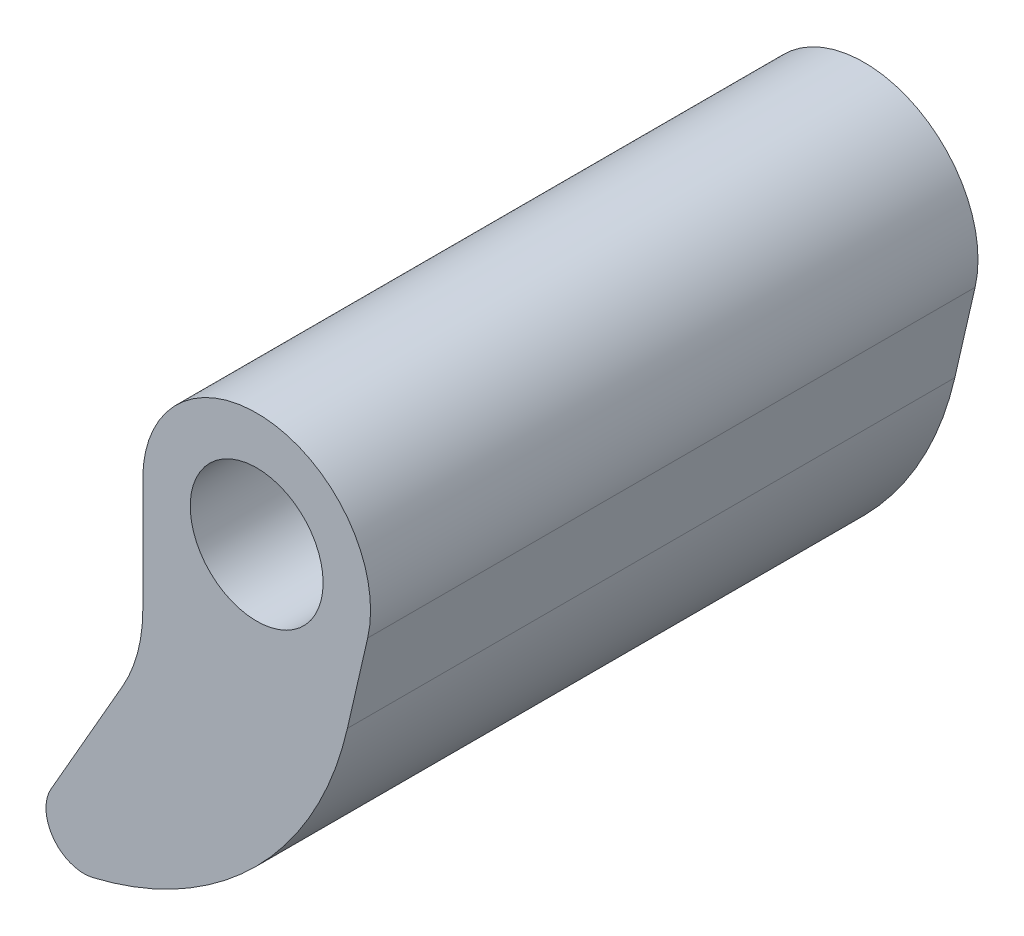
SolidWorks part; units mm, degrees
ref_plane "Front Plane" through (0, 0, 0) normal (0, 0, 1) x (1, 0, 0)
ref_plane "Top Plane" through (0, 0, 0) normal (0, 1, 0) x (1, 0, 0)
ref_plane "Right Plane" through (0, 0, 0) normal (1, 0, 0) x (0, 0, -1)
sketch "Sketch1" plane through (0, 0, 0) normal (0, 0, 1) x (1, 0, 0)
  line L0 (1.462, -0.3357) -> (1.1946, -1.5)
  line L1 (1.1946, -1.5) -> (-1.5, -1.5) construction
  line L2 (-1.5, -1.5) -> (-1.5, 0)
  line L5 (0, 0) -> (0, -0.875) construction
  line L6 (-3.2, -5) -> (3.326, -5) construction
  line L7 (-1.7664, -2.5) -> (-2.7086, -4.1431)
  arc A0 (1.462, -0.3357) -> (-1.5, 0) centre (0, 0) ccw
  circle A1 centre (0, 0) radius 0.875
  arc A2 (-1.5, -1.5) -> (-1.7664, -2.5) centre (-3.5102, -1.5) cw
  arc A4 (-2.1595, -4.8783) -> (-2.7086, -4.1431) centre (-2.2748, -4.3918) cw
  arc A5 (1.1946, -1.5) -> (-2.1595, -4.8783) centre (-3.2, -0.491) cw
  dimension "D1" = 1.75
  dimension "D2" = 3
  dimension "D9" = 0.5
  dimension "D3" = 1
  dimension "D4" = 5
  dimension "D5" = 3.2
extrude "Boss-Extrude1" add sketch "Sketch1" along normal blind 8
